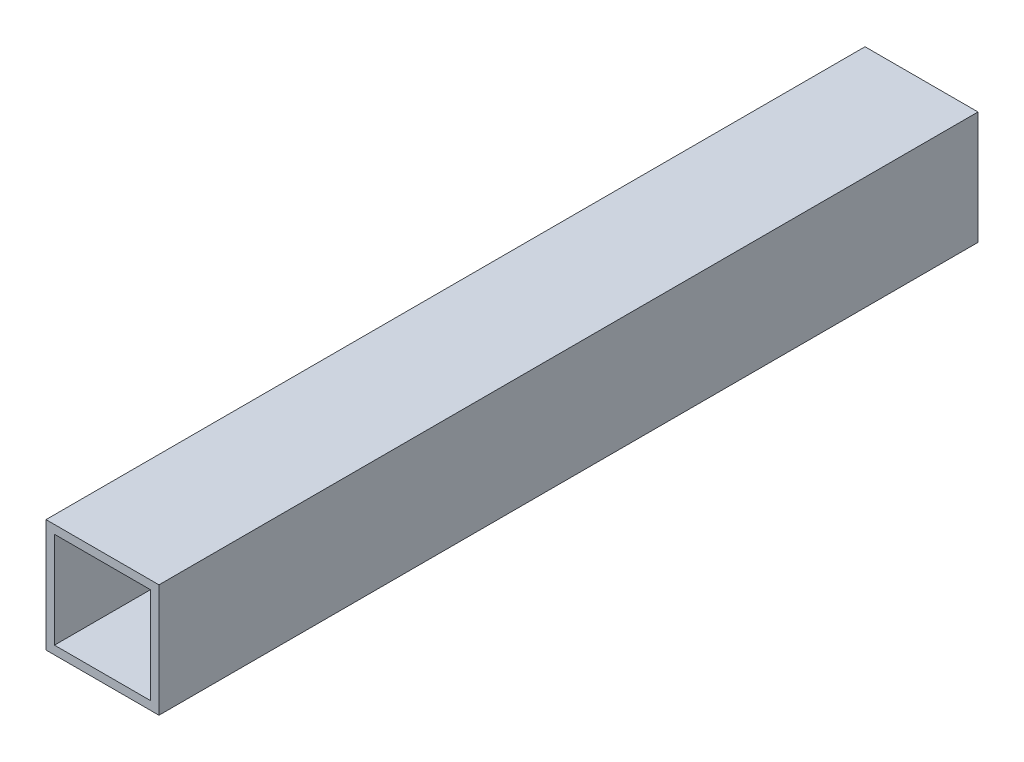
SolidWorks part; units mm, degrees
ref_plane "Alzado" through (0, 0, 0) normal (0, 0, 1) x (1, 0, 0)
ref_plane "Planta" through (0, 0, 0) normal (0, 1, 0) x (1, 0, 0)
ref_plane "Vista lateral" through (0, 0, 0) normal (1, 0, 0) x (0, 0, -1)
sketch "Croquis1" plane through (0, 0, 0) normal (0, 0, 1) x (1, 0, 0)
  line L0 (-10, -10) -> (-10, 10)
  line L1 (-8.5, -8.5) -> (8.5, -8.5)
  line L2 (-8.5, -8.5) -> (-8.5, 8.5)
  line L3 (-8.5, 8.5) -> (8.5, 8.5)
  line L4 (8.5, -8.5) -> (8.5, 8.5)
  line L5 (-8.5, -8.5) -> (8.5, 8.5) construction
  line L6 (-8.5, 8.5) -> (8.5, -8.5) construction
  line L7 (-10, 10) -> (10, 10)
  line L8 (10, -10) -> (10, 10)
  line L9 (-10, -10) -> (10, -10)
  point P0 (0, 0)
  dimension "D2" = 20
  dimension "D3" = 20
  dimension "D1" = 1.5
extrude "Saliente-Extruir1" add sketch "Croquis1" along normal mid plane 145
